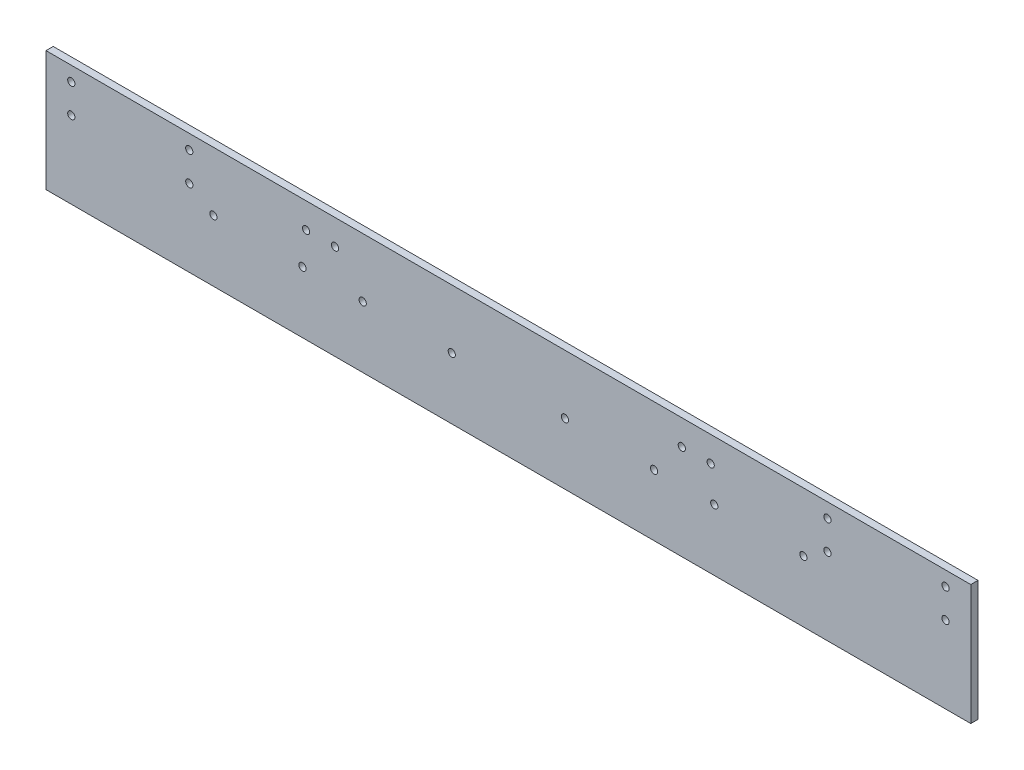
SolidWorks part; units mm, degrees
ref_plane "前视基准面" through (0, 0, 0) normal (0, 0, 1) x (1, 0, 0)
ref_plane "上视基准面" through (0, 0, 0) normal (0, 1, 0) x (1, 0, 0)
ref_plane "右视基准面" through (0, 0, 0) normal (1, 0, 0) x (0, 0, -1)
sketch "草图1" plane through (0, 0, 0) normal (0, 0, 1) x (1, 0, 0)
  line L1 (0, 0) -> (384, 0)
  line L2 (0, 0) -> (0, 50)
  line L3 (0, 50) -> (384, 50)
  line L4 (384, 0) -> (384, 50)
  dimension "D1" = 384
  dimension "D2" = 50
extrude "凸台-拉伸1" add sketch "草图1" along normal blind 3
sketch "草图2" plane through (0, 0, 3) normal (0, 0, 1) x (1, 0, 0)
  line L0 (192, 50) -> (192, 0) construction
  line L1 (384, 50) -> (0, 50) construction
  line L2 (0, 0) -> (384, 0) construction
  line L3 (384, 0) -> (384, 50) construction
  circle A0 centre (264, 39.5) radius 1.5
  circle A1 centre (276, 39.5) radius 1.5
  circle A2 centre (120, 39.5) radius 1.5
  circle A3 centre (108, 39.5) radius 1.5
  circle A4 centre (215.5, 25.5) radius 1.5
  circle A5 centre (252.5, 25.5) radius 1.5
  circle A6 centre (277.5, 25.5) radius 1.5
  circle A7 centre (314.5, 25.5) radius 1.5
  circle A8 centre (69.5, 25.5) radius 1.5
  circle A9 centre (106.5, 25.5) radius 1.5
  circle A10 centre (131.5, 25.5) radius 1.5
  circle A11 centre (168.5, 25.5) radius 1.5
  circle A12 centre (373.5, 44) radius 1.5
  circle A13 centre (373.5, 32) radius 1.5
  circle A14 centre (324.5, 44) radius 1.5
  circle A15 centre (324.5, 32) radius 1.5
  circle A16 centre (59.5, 44) radius 1.5
  circle A17 centre (10.5, 44) radius 1.5
  circle A18 centre (10.5, 32) radius 1.5
  circle A19 centre (59.5, 32) radius 1.5
  dimension "D6" = 3
  dimension "D11" = 3
  dimension "D17" = 3
  dimension "D1" = 72
  dimension "D2" = 12
  dimension "D3" = 10.5
  dimension "D4" = 72
  dimension "D5" = 12
  dimension "D7" = 37
  dimension "D8" = 37
  dimension "D9" = 25
  dimension "D10" = 23.5
  dimension "D12" = 24.5
  dimension "D13" = 10.5
  dimension "D14" = 59.5
  dimension "D15" = 6
  dimension "D16" = 12
extrude "切除-拉伸1" cut sketch "草图2" against normal through all
